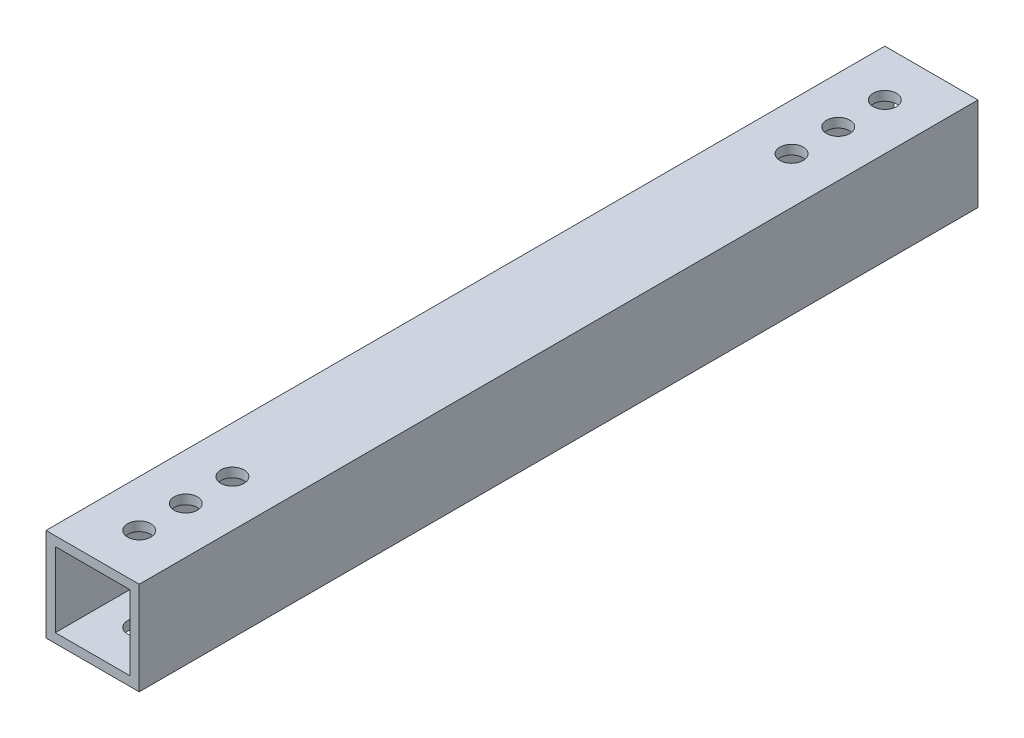
SolidWorks part; units mm, degrees
ref_plane "Front Plane" through (0, 0, 0) normal (0, 0, 1) x (1, 0, 0)
ref_plane "Top Plane" through (0, 0, 0) normal (0, 1, 0) x (1, 0, 0)
ref_plane "Right Plane" through (0, 0, 0) normal (1, 0, 0) x (0, 0, -1)
sketch "Sketch1" plane through (0, 0, 0) normal (0, 0, 1) x (1, 0, 0)
  line L0 (-10.16, 10.16) -> (10.16, 10.16)
  line L1 (-12.7, -12.7) -> (12.7, -12.7)
  line L2 (-12.7, -12.7) -> (-12.7, 12.7)
  line L3 (-12.7, 12.7) -> (12.7, 12.7)
  line L4 (12.7, -12.7) -> (12.7, 12.7)
  line L5 (-12.7, -12.7) -> (12.7, 12.7) construction
  line L6 (-12.7, 12.7) -> (12.7, -12.7) construction
  line L7 (10.16, -10.16) -> (10.16, 10.16)
  line L8 (-10.16, -10.16) -> (10.16, -10.16)
  line L9 (-10.16, -10.16) -> (-10.16, 10.16)
  point P0 (0, 0)
  dimension "D1" = 25.4
  dimension "D2" = 25.4
  dimension "D3" = 2.54
extrude "Boss-Extrude2" add sketch "Sketch1" along normal blind 228.6
sketch "Sketch2" plane through (0, 12.7, 0) normal (0, 1, 0) x (1, 0, 0)
  line L0 (-12.7, -228.6) -> (12.7, -213.9353)
  line L1 (12.7, -228.6) -> (12.7, 0) construction
  line L2 (12.7, -213.9353) -> (12.7, -228.6)
  line L3 (12.7, -228.6) -> (-12.7, -228.6)
  line L4 (-12.7, -114.3) -> (12.7, -114.3) construction
  line L5 (-12.7, -228.6) -> (-12.7, 0) construction
  line L6 (12.7, 0) -> (-12.7, 0)
  line L7 (12.7, -14.6647) -> (12.7, 0)
  line L8 (-12.7, 0) -> (12.7, -14.6647)
  dimension "D1" = 30
extrude "Cut-Extrude1" [suppressed] cut sketch "Sketch2" against normal through all
sketch "Sketch3" plane through (0, 12.7, 0) normal (0, 1, 0) x (1, 0, 0)
  line L0 (0, 0) -> (0, -228.6) construction
  line L1 (12.7, -228.6) -> (-12.7, -228.6) construction
  line L2 (12.7, 0) -> (-12.7, 0) construction
  line L3 (-12.7, -114.3) -> (12.7, -114.3) construction
  line L4 (-12.7, -228.6) -> (-12.7, 0) construction
  line L5 (12.7, -228.6) -> (12.7, 0) construction
  circle A0 centre (0, -12.7) radius 3.175
  circle A1 centre (0, -25.4) radius 3.175
  circle A2 centre (0, -38.1) radius 3.175
  circle A3 centre (0, -190.5) radius 3.175
  circle A4 centre (0, -203.2) radius 3.175
  circle A5 centre (0, -215.9) radius 3.175
  dimension "D1" = 6.35
  dimension "D2" = 12.7
  dimension "D3" = 3
extrude "Cut-Extrude2" cut sketch "Sketch3" against normal through all
